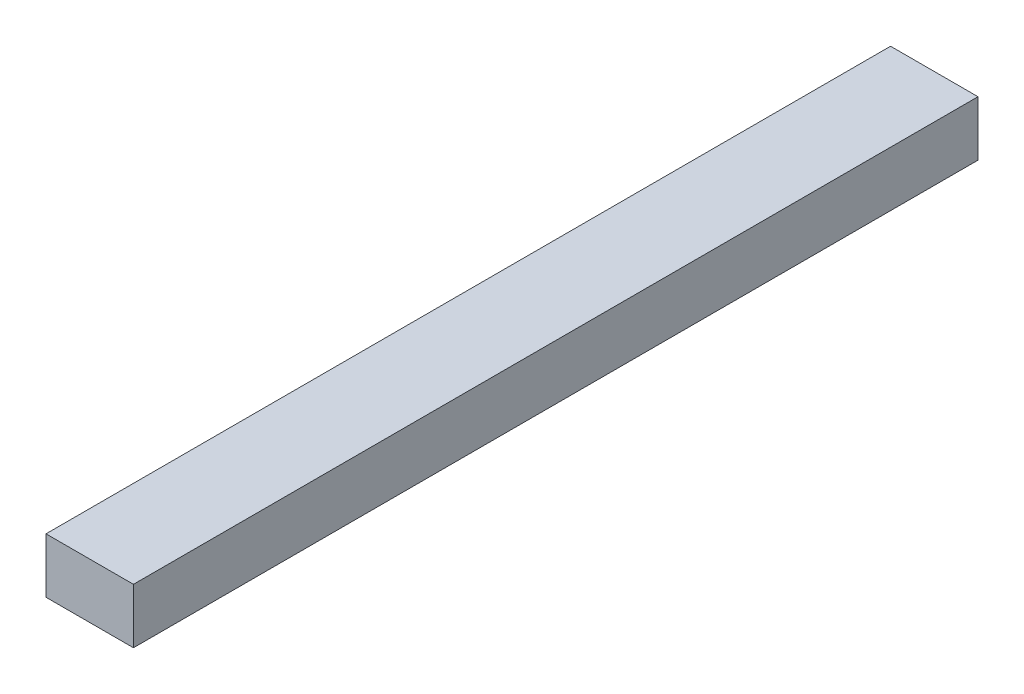
SolidWorks part; units mm, degrees
ref_plane "Front Plane" through (0, 0, 0) normal (0, 0, 1) x (1, 0, 0)
ref_plane "Top Plane" through (0, 0, 0) normal (0, 1, 0) x (1, 0, 0)
ref_plane "Right Plane" through (0, 0, 0) normal (1, 0, 0) x (0, 0, -1)
sketch "Sketch1" plane through (0, 0, 0) normal (0, 0, 1) x (1, 0, 0)
  line L7 (-35, -22) -> (35, -22)
  line L8 (-35, -22) -> (-35, 22)
  line L9 (-35, 22) -> (35, 22)
  line L10 (35, -22) -> (35, 22)
  line L11 (-35, -22) -> (35, 22) construction
  line L12 (-35, 22) -> (35, -22) construction
  point P10 (0, 0)
  dimension "D1" = 70
  dimension "D2" = 44
extrude "Boss-Extrude1" add sketch "Sketch1" along a picked direction on the side of the normal mid plane 676
